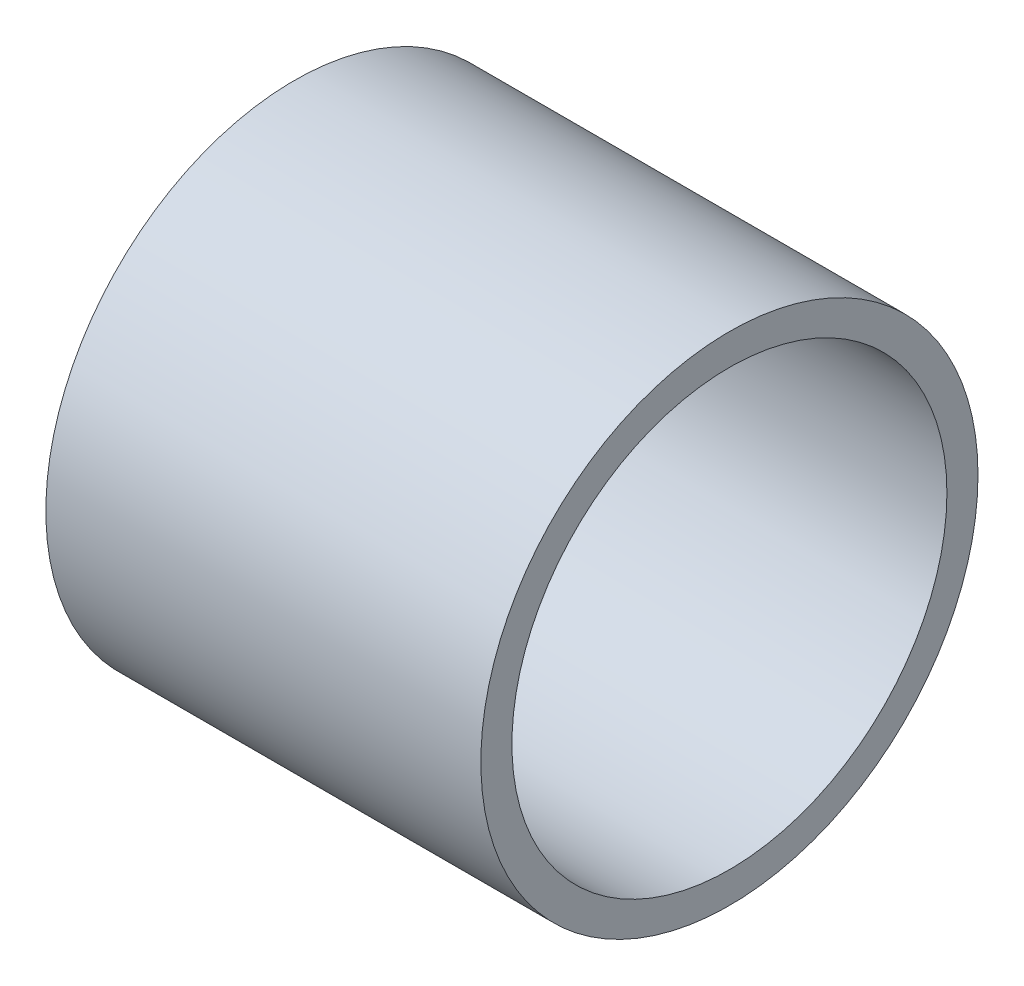
SolidWorks part; units mm, degrees
ref_plane "Alzado" through (0, 0, 0) normal (0, 0, 1) x (1, 0, 0)
ref_plane "Planta" through (0, 0, 0) normal (0, 1, 0) x (1, 0, 0)
ref_plane "Vista lateral" through (0, 0, 0) normal (1, 0, 0) x (0, 0, -1)
sketch "Croquis1" plane through (0, 0, 0) normal (1, 0, 0) x (0, 0, -1)
  circle A1 centre (0, 0) radius 14
  circle A2 centre (0, 0) radius 16
  dimension "D2" = 28
  dimension "D3" = 32
extrude "Saliente-Extruir1" add sketch "Croquis1" along normal blind 28
sketch "Croquis2" plane through (0, 0, 0) normal (1, 0, 0) x (0, 0, -1)
  circle A0 centre (0, 0) radius 14
  circle A1 centre (0, 0) radius 9
  dimension "D1" = 18
extrude "Saliente-Extruir2" add sketch "Croquis2" along normal blind 2
